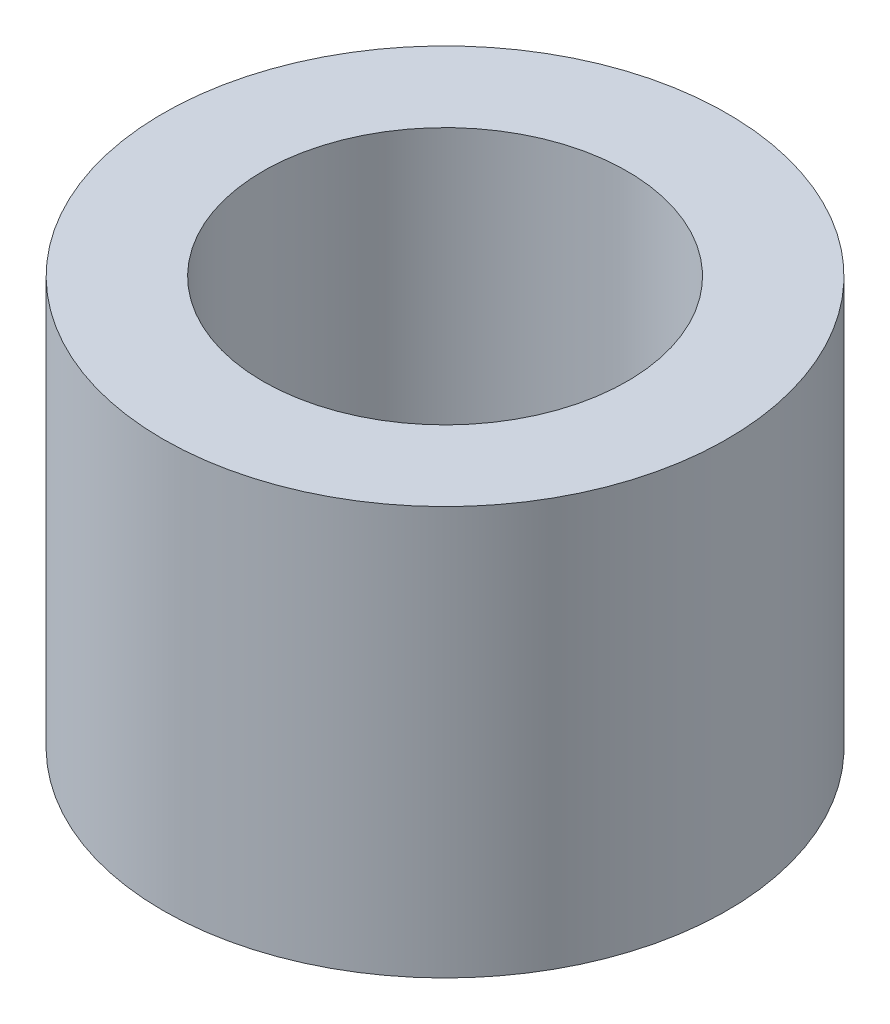
SolidWorks part; units mm, degrees
material "Brass"
ref_plane "Front Plane" through (0, 0, 0) normal (0, 0, 1) x (1, 0, 0)
ref_plane "Top Plane" through (0, 0, 0) normal (0, 1, 0) x (1, 0, 0)
ref_plane "Right Plane" through (0, 0, 0) normal (1, 0, 0) x (0, 0, -1)
sketch "Sketch1" plane through (0, 0, 0) normal (0, 1, 0) x (1, 0, 0)
  circle A0 centre (0, 0) radius 5.6642
  circle A1 centre (0, 0) radius 8.7757
  dimension "D1" = 11.3284
  dimension "D2" = 17.5514
extrude "Boss-Extrude1" add sketch "Sketch1" along normal blind 12.7
